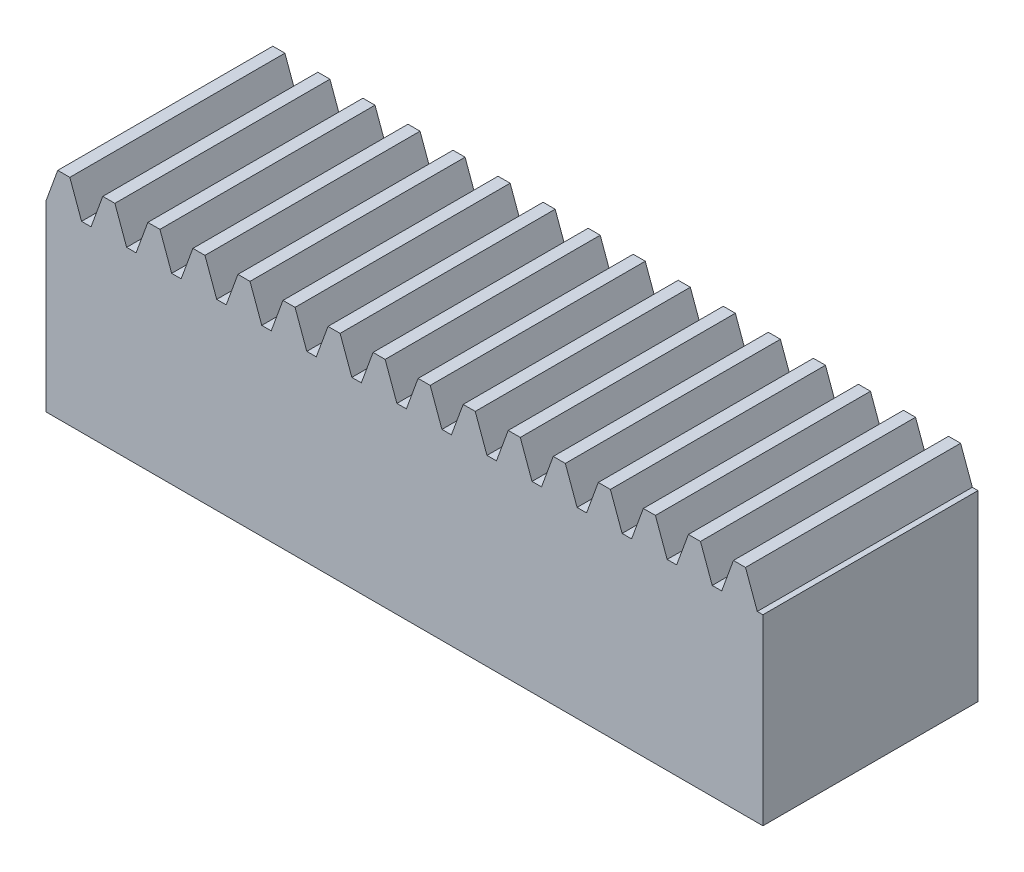
SolidWorks part; units mm, degrees
ref_plane "前视基准面" through (0, 0, 0) normal (0, 0, 1) x (1, 0, 0)
ref_plane "上视基准面" through (0, 0, 0) normal (0, 1, 0) x (1, 0, 0)
ref_plane "右视基准面" through (0, 0, 0) normal (1, 0, 0) x (0, 0, -1)
sketch "草图1" plane through (0, 0, 0) normal (0, 0, 1) x (1, 0, 0)
  line L1 (0, 0) -> (50, 0)
  line L2 (0, 0) -> (0, -12.75)
  line L3 (0, -12.75) -> (50, -12.75)
  line L4 (50, 0) -> (50, -12.75)
  dimension "D1" = 12.75
  dimension "L" = 50
extrude "拉伸1" add sketch "草图1" along normal blind 15
sketch "草图2" plane through (0, 0, 15) normal (0, 0, 1) x (1, 0, 0)
  line L0 (0, 0) -> (0.8189, 2.25)
  line L1 (0.8189, 2.25) -> (1.6618, 2.25)
  line L2 (1.6618, 2.25) -> (2.4807, 0)
  line L3 (50, 0) -> (0, 0) construction
  line L4 (0, 0) -> (2.4807, 0)
  line L5 (0.455, 1.25) -> (2.0258, 1.25) construction
  dimension "D2" = 70
  dimension "alpha" = 110
  dimension "ha" = 1
  dimension "hf" = 1.25
  dimension "S" = 1.5708
extrude "拉伸2" add sketch "草图2" against normal up to surface (15 mm away) up to face at (25, -6.375, 0)
pattern_linear "阵列(线性)1" count 16 spacing 3.1416 along (1, 0, 0) of "拉伸2"
equation "\"d\"=\"S@草图2\" * 2"
equation "\"z\"= int(  \"L@草图1\" / (  \"S@草图2\" * 2 ) + 0.5 )"
